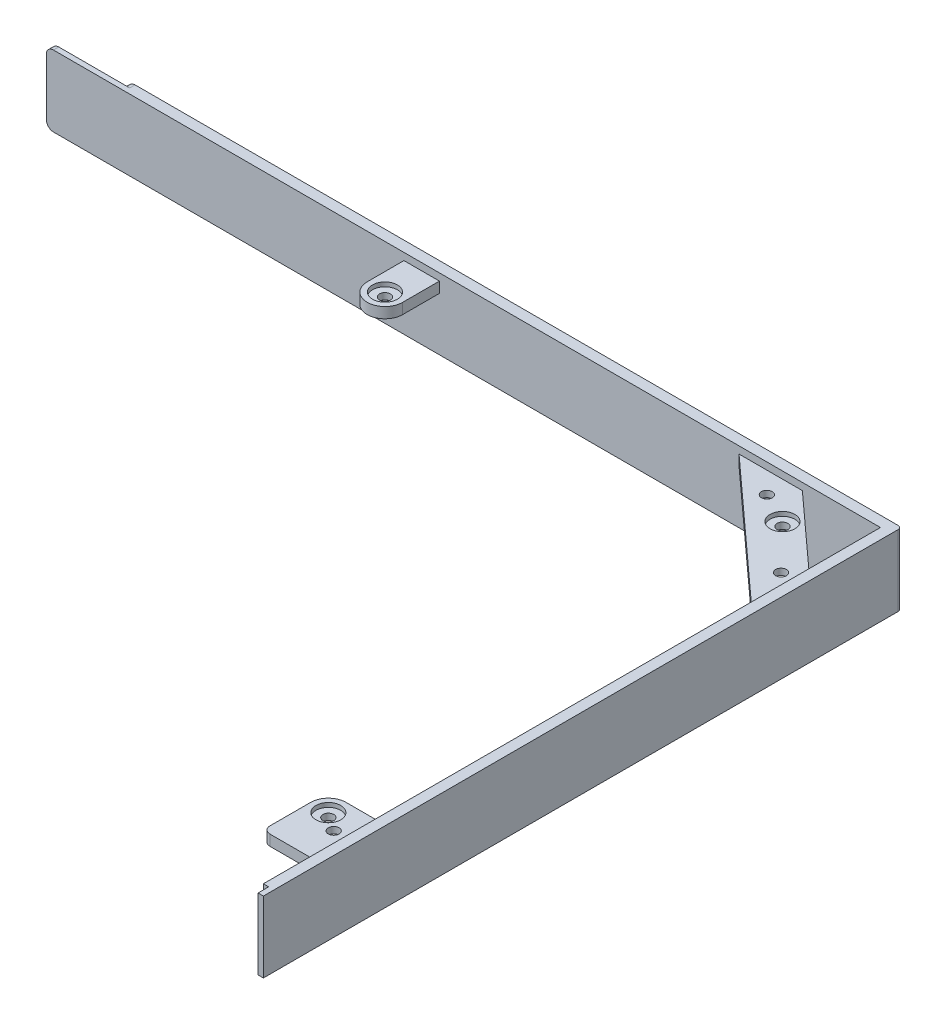
SolidWorks part; units mm, degrees
ref_plane "前视基准面" through (0, 0, 0) normal (0, 0, 1) x (1, 0, 0)
ref_plane "上视基准面" through (0, 0, 0) normal (0, 1, 0) x (1, 0, 0)
ref_plane "右视基准面" through (0, 0, 0) normal (1, 0, 0) x (0, 0, -1)
other "Configuration Table"
sketch "草图1" plane through (0, 0, 0) normal (0, 1, 0) x (1, 0, 0)
  line L0 (1.5, 0) -> (3, 0)
  line L1 (3, 0) -> (3, 173.85)
  line L2 (3, 173.85) -> (307.4, 173.85)
  line L3 (307.4, 173.85) -> (307.4, 176.85)
  line L4 (307.4, 176.85) -> (0, 176.85)
  line L5 (0, 176.85) -> (0, 0)
  line L6 (0, 0) -> (0, -3)
  line L7 (0, -3) -> (1.5, -3)
  line L8 (1.5, -3) -> (1.5, 0)
  dimension "D1" = 304.4
  dimension "D2" = 173.85
  dimension "D3" = 3
  dimension "D4" = 3
  dimension "D5" = 3
extrude "凸台-拉伸1" add sketch "草图1" along normal blind 20
ref_plane "基准面1" through (0, 14, 0) normal (0, 1, 0) x (1, 0, 0)
sketch "草图2" plane through (0, 14, 0) normal (0, 1, 0) x (1, 0, 0)
  line L0 (307.4, -177.55) -> (307.4, -138.0563) construction
  line L1 (3, 173.85) -> (611.8, 173.85) construction
  line L2 (3, 173.85) -> (3, -181.25) construction
  line L3 (3, -181.25) -> (611.8, -181.25) construction
  line L4 (611.8, 173.85) -> (611.8, -181.25) construction
  line L5 (611.8, 0) -> (505.4057, 0) construction
  line L6 (3, 153.85) -> (25, 173.85)
  line L7 (42.8393, 173.85) -> (3, 137.6325)
  line L8 (3, 173.85) -> (307.4, 173.85) construction
  line L9 (3, 0) -> (3, 173.85) construction
  line L10 (42.8393, 173.85) -> (25, 173.85)
  line L11 (3, 137.6325) -> (3, 153.85)
  line L12 (137.25, 163.5) -> (137.25, 173.85)
  line L13 (127.25, 163.5) -> (127.25, 173.85)
  line L14 (127.25, 173.85) -> (137.25, 173.85)
  line L16 (3, 23.8703) -> (3, 33.5)
  line L17 (3, 33.5) -> (13.2, 33.5)
  line L18 (18.2, 28.5) -> (18.2, 15.044)
  line L19 (18.2, 15.044) -> (3, 15.044)
  line L20 (3, 15.044) -> (3, 23.8703)
  circle A0 centre (20.25, 163.5) radius 1.525
  circle A1 centre (132.25, 163.5) radius 1.525
  arc A2 (127.25, 163.5) -> (137.25, 163.5) centre (132.25, 163.5) ccw
  circle A3 centre (13.2, 28.5) radius 1.525
  arc A4 (18.2, 28.5) -> (13.2, 33.5) centre (13.2, 28.5) ccw
  dimension "D3" = 3.05
  dimension "D9" = 3.05
  dimension "D10" = 10
  dimension "D13" = 3.05
  dimension "D15" = 10
  dimension "D1" = 608.8
  dimension "D2" = 355.1
  dimension "D4" = 287.15
  dimension "D5" = 163.5
  dimension "D6" = 22
  dimension "D7" = 20
  dimension "D8" = 12
  dimension "D11" = 163.5
  dimension "D12" = 175.15
  dimension "D14" = 28.5
  dimension "D16" = 294.2
  dimension "D17" = 173.85
extrude "凸台-拉伸2" add sketch "草图2" along normal blind 3 from offset 1
sketch "草图3" plane through (0, 0, -176.85) normal (0, 0, -1) x (-1, 0, 0)
  line L0 (-276.4, 10.5) -> (-307.4, 10.5)
  line L1 (-307.4, 0) -> (0, 0) construction
  line L2 (-307.4, 20) -> (-307.4, 0) construction
  line L3 (-276.4, 10.5) -> (-276.4, 20)
  line L4 (-307.4, 20) -> (0, 20) construction
  line L5 (-276.4, 20) -> (-307.4, 20)
  line L6 (-307.4, 20) -> (-307.4, 10.5)
  dimension "D1" = 10.5
  dimension "D2" = 31
extrude "切除-拉伸1" cut sketch "草图3" against normal up to next
ref_plane "基准面2" through (317.4, 0, 0) normal (1, 0, 0) x (0, 0, -1)
sketch "草图4" plane through (0, 18, 0) normal (0, 1, 0) x (1, 0, 0)
  circle A0 centre (13.2, 28.5) radius 3.5
  circle A1 centre (20.25, 163.5) radius 3.5
  circle A2 centre (132.25, 163.5) radius 3.5
  dimension "D1" = 7
  dimension "D2" = 7
  dimension "D3" = 7
extrude "切除-拉伸2" cut sketch "草图4" against normal blind 1.2
sketch "草图5" plane through (0, 15, 0) normal (0, -1, 0) x (1, 0, 0)
  line L0 (132.25, -163.5) -> (132.25, -166.8465) construction
  line L1 (3, -173.85) -> (307.4, -173.85) construction
  line L2 (132.25, -167.85) -> (75.3924, -167.85) construction
  line L3 (3, 0) -> (3, -173.85) construction
  line L4 (13.2, -28.5) -> (9.8492, -28.5) construction
  line L5 (8, -28.5) -> (8, -37.2968) construction
  line L7 (3, -173.85) -> (276.4, -173.85) construction
  circle A1 centre (29, -167.85) radius 1.525
  circle A3 centre (8, -150.85) radius 1.525
  circle A4 centre (8, -24.8) radius 1.525
  dimension "D3" = 3.05
  dimension "D5" = 3.05
  dimension "D7" = 3.05
  dimension "D4" = 26
  dimension "D6" = 149.05
  dimension "D8" = 23
extrude "切除-拉伸3" cut sketch "草图5" against normal up to next
fillet "圆角1" radius 1 1 edges at (0, 10, -176.85)
fillet "圆角3" radius 1 1 edges at (276.4, 10.5, -175.35)
sketch "草图6" plane through (0, 15, 0) normal (0, -1, 0) x (1, 0, 0)
  circle A0 centre (8, -24.8) radius 3.5
  circle A1 centre (8, -150.85) radius 3.5
  circle A2 centre (29, -167.85) radius 3.5
  dimension "D1" = 7
  dimension "D2" = 7
  dimension "D3" = 7
extrude "切除-拉伸4" cut sketch "草图6" against normal blind 1.2
sketch "草图7" plane through (0, 0, -176.85) normal (0, 0, -1) x (-1, 0, 0)
  line L0 (0, 20) -> (0, 0) construction
  line L2 (-276.4, 20) -> (-1, 20) construction
  line L4 (-238, 0) -> (-307.4, 0)
  line L5 (-238, 0) -> (-238, 20)
  line L6 (-238, 20) -> (-307.4, 20)
  line L7 (-307.4, 0) -> (-307.4, 20)
  dimension "D1" = 238
extrude "切除-拉伸5" cut sketch "草图7" against normal blind 3
mirror "镜向3" about plane through (317.4, 0, 0) normal (1, 0, 0) of bodies 121
delete or keep bodies "实体-删除/保留 1" type keep bodies bodies 123
sketch "草图8" plane through (0, 0, -176.85) normal (0, 0, -1) x (-1, 0, 0)
  line L0 (-396.8, 20) -> (-633.8, 20) construction
  line L1 (-396.8, 0) -> (-416.8, 0)
  line L2 (-396.8, 0) -> (-396.8, 20)
  line L3 (-396.8, 20) -> (-416.8, 20)
  line L4 (-416.8, 0) -> (-416.8, 20)
  dimension "D1" = 20
extrude "切除-拉伸6" cut sketch "草图8" against normal blind 1.5
fillet "圆角4" radius 2 2 edges at (416.8, 0, -176.1) (416.8, 20, -176.1)
fillet "圆角5" radius 2 2 edges at (396.8, 0, -174.6) (396.8, 20, -174.6)
fillet "圆角6" radius 2 1 edges at (616.6, 16.5, -15.044)
